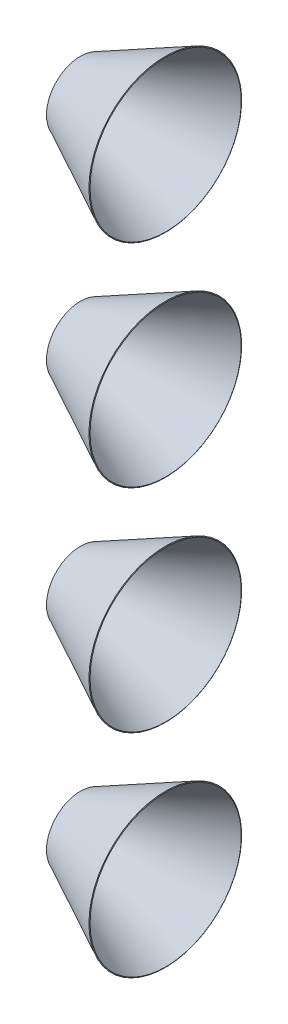
SolidWorks part; units mm, degrees
ref_plane "前视基准面" through (0, 0, 0) normal (0, 0, 1) x (1, 0, 0)
ref_plane "上视基准面" through (0, 0, 0) normal (0, 1, 0) x (1, 0, 0)
ref_plane "右视基准面" through (0, 0, 0) normal (1, 0, 0) x (0, 0, -1)
sketch "草图1" plane through (0, 0, 0) normal (0, 0, 1) x (1, 0, 0)
  line L0 (1200, -375) -> (1300, -375)
  line L1 (1200, -335) -> (1300, -285)
revolve "旋转-薄壁1" add sketch "草图1" angle 360 about L0
sketch "草图2" plane through (0, 0, 0) normal (0, 0, 1) x (1, 0, 0)
  line L0 (1200, -125) -> (1300, -125)
  line L1 (1200, -85) -> (1300, -35)
revolve "旋转-薄壁2" add sketch "草图2" angle 360 about L0
sketch "草图3" plane through (0, 0, 0) normal (0, 0, 1) x (1, 0, 0)
  line L0 (1200, 125) -> (1300, 125)
  line L1 (1200, 165) -> (1300, 215)
revolve "旋转-薄壁3" add sketch "草图3" angle 360 about L0
sketch "草图4" plane through (0, 0, 0) normal (0, 0, 1) x (1, 0, 0)
  line L0 (1200, 375) -> (1300, 375)
  line L1 (1200, 415) -> (1300, 465)
revolve "旋转-薄壁4" add sketch "草图4" angle 360 about L0
